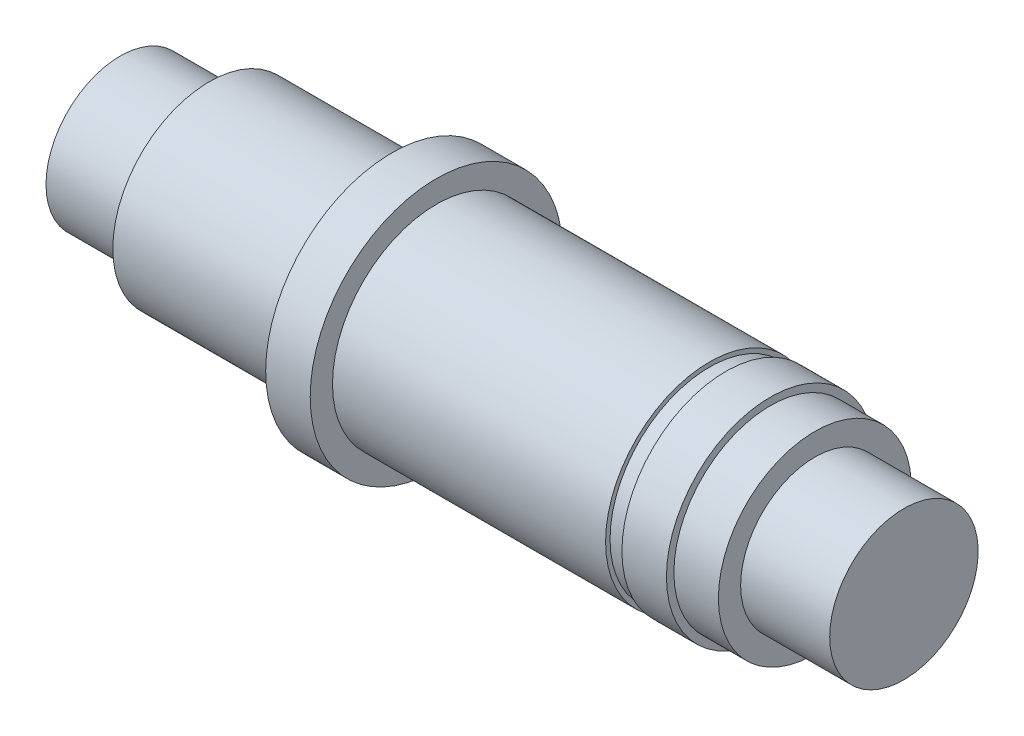
SolidWorks part; units mm, degrees
ref_plane "Front Plane" through (0, 0, 0) normal (0, 0, 1) x (1, 0, 0)
ref_plane "Top Plane" through (0, 0, 0) normal (0, 1, 0) x (1, 0, 0)
ref_plane "Right Plane" through (0, 0, 0) normal (1, 0, 0) x (0, 0, -1)
sketch "Sketch1" plane through (0, 0, 0) normal (0, 0, 1) x (1, 0, 0)
  line L0 (-13.6685, 0) -> (51.2825, 0) construction
  line L1 (0, 0) -> (0, 5)
  line L2 (0, 5) -> (6, 5)
  line L3 (6, 5) -> (6, 6.5)
  line L4 (6, 6.5) -> (18.3, 6.5)
  line L5 (18.3, 6.5) -> (18.3, 8.5)
  line L6 (18.3, 8.5) -> (21.3, 8.5)
  line L7 (21.3, 8.5) -> (21.3, 7)
  line L8 (21.3, 7) -> (39.7, 7)
  line L10 (46.8, 5) -> (52.8, 5)
  line L11 (52.8, 5) -> (52.8, 0)
  line L12 (0, 0) -> (52.8, 0)
  line L13 (39.7, 7) -> (39.7, 6.7)
  line L14 (39.7, 6.7) -> (40.8, 6.7)
  line L15 (40.8, 6.7) -> (40.8, 7)
  line L19 (40.8, 7) -> (43.8, 7)
  line L20 (43.8, 7) -> (43.8, 6.5)
  line L22 (43.8, 6.5) -> (46.8, 6.5)
  line L23 (46.8, 6.5) -> (46.8, 5)
  dimension "D1" = 5
  dimension "D2" = 6.5
  dimension "D3" = 12.3
  dimension "D4" = 6
  dimension "D5" = 3
  dimension "D6" = 6.5
  dimension "D7" = 7
  dimension "D8" = 3
  dimension "D9" = 3
  dimension "D10" = 2
  dimension "D11" = 6.7
  dimension "D12" = 1.1
  dimension "D13" = 21.4
revolve "Revolve1" add sketch "Sketch1" angle 360 about L0
